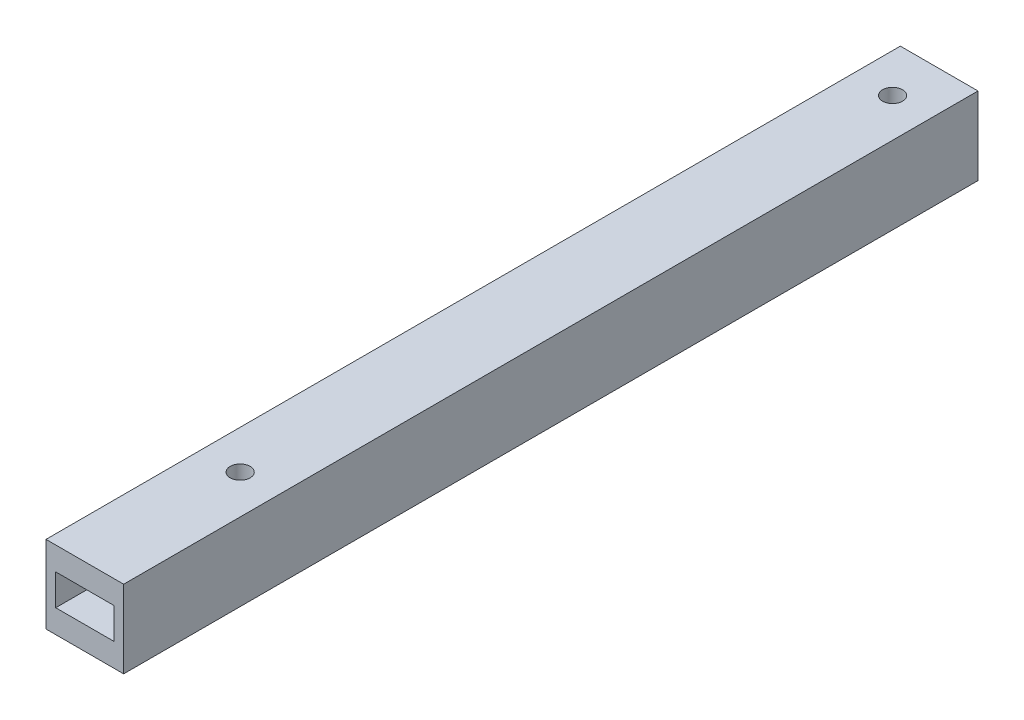
SolidWorks part; units mm, degrees
material "1060 Alloy"
ref_plane "Front Plane" through (0, 0, 0) normal (0, 0, 1) x (1, 0, 0)
ref_plane "Top Plane" through (0, 0, 0) normal (0, 1, 0) x (1, 0, 0)
ref_plane "Right Plane" through (0, 0, 0) normal (1, 0, 0) x (0, 0, -1)
sketch "Sketch2" plane through (0, 0, 0) normal (0, 0, 1) x (1, 0, 0)
  line L1 (12.7, -12.7) -> (-12.7, -12.7)
  line L2 (12.7, -12.7) -> (12.7, 12.7)
  line L3 (12.7, 12.7) -> (-12.7, 12.7)
  line L4 (-12.7, -12.7) -> (-12.7, 12.7)
  line L5 (12.7, -12.7) -> (-12.7, 12.7) construction
  line L6 (12.7, 12.7) -> (-12.7, -12.7) construction
  point P0 (0, 0)
  dimension "D1" = 25.4
extrude "Boss-Extrude1" add sketch "Sketch2" along normal blind 279.4 contours L4 L3 L2 L1
sketch "Sketch4" plane through (0, 0, 0) normal (0, 0, 1) x (1, 0, 0)
  line L0 (12.7, -12.7) -> (12.7, 12.7) construction
  line L1 (-9.525, -5.08) -> (9.525, -5.08)
  line L2 (-9.525, -5.08) -> (-9.525, 5.08)
  line L3 (-9.525, 5.08) -> (9.525, 5.08)
  line L4 (9.525, -5.08) -> (9.525, 5.08)
  line L5 (-9.525, -5.08) -> (9.525, 5.08) construction
  line L6 (-9.525, 5.08) -> (9.525, -5.08) construction
  line L7 (12.7, 12.7) -> (-12.7, 12.7) construction
  point P0 (0, 0)
  dimension "D1" = 3.175
  dimension "D2" = 7.62
extrude "Cut-Extrude1" cut sketch "Sketch4" along normal through all
sketch "Sketch5" plane through (0, 12.7, 0) normal (0, 1, 0) x (1, 0, 0)
  line L0 (12.7, 0) -> (-12.7, 0) construction
  circle A0 centre (0, -15.24) radius 3.2639
  point P5 (0, 0)
  dimension "D1" = 6.5278
  dimension "D2" = 15.24
extrude "Cut-Extrude2" cut sketch "Sketch5" against normal through all
sketch "Sketch6" plane through (0, 12.7, 0) normal (0, 1, 0) x (1, 0, 0)
  line L0 (12.7, -279.4) -> (-12.7, -279.4) construction
  circle A0 centre (0, -228.6) radius 3.2639
  point P4 (0, -279.4)
  dimension "D1" = 6.5278
  dimension "D2" = 50.8
extrude "Cut-Extrude3" cut sketch "Sketch6" against normal through all
